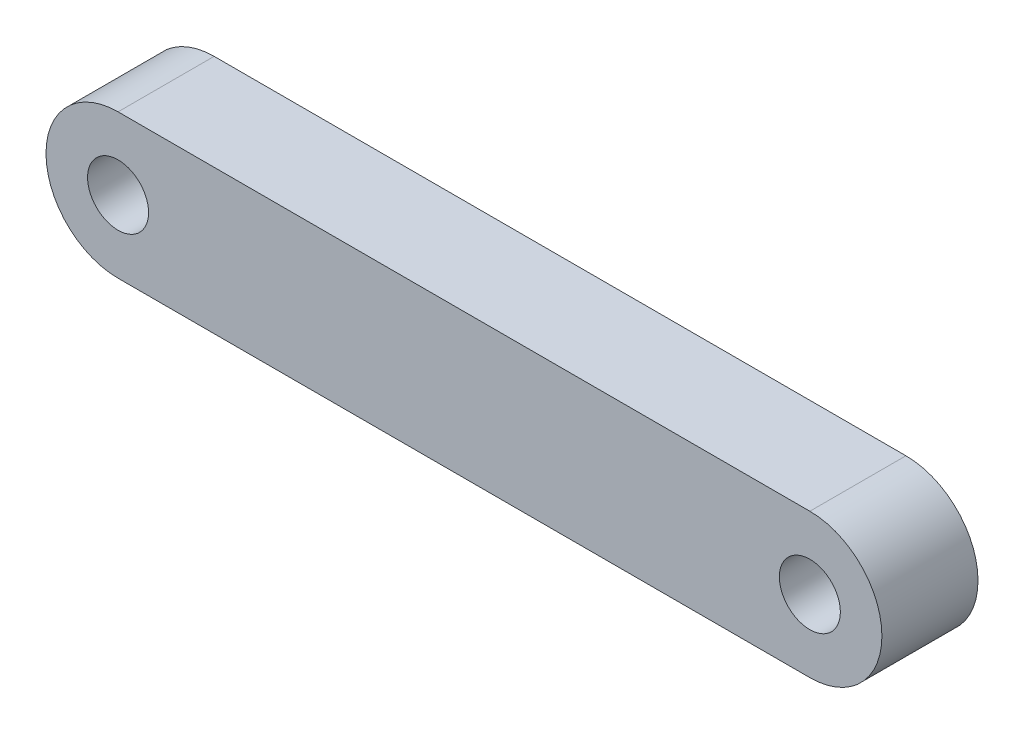
SolidWorks part; units mm, degrees
ref_plane "Front Plane" through (0, 0, 0) normal (0, 0, 1) x (1, 0, 0)
ref_plane "Top Plane" through (0, 0, 0) normal (0, 1, 0) x (1, 0, 0)
ref_plane "Right Plane" through (0, 0, 0) normal (1, 0, 0) x (0, 0, -1)
sketch "Sketch1" plane through (0, 0, 0) normal (0, 0, 1) x (1, 0, 0)
  line L0 (-18, 0) -> (18, 0) construction
  line L1 (-18, 3.75) -> (18, 3.75)
  line L2 (-18, -3.75) -> (18, -3.75)
  arc A0 (-18, 3.75) -> (-18, -3.75) centre (-18, 0) ccw
  arc A1 (18, -3.75) -> (18, 3.75) centre (18, 0) ccw
  point P3 (0, 0)
  dimension "D1" = 36
  dimension "D2" = 7.5
extrude "Boss-Extrude1" add sketch "Sketch1" along normal mid plane 5
sketch "Sketch2" plane through (0, 0, 2.5) normal (0, 0, 1) x (1, 0, 0)
  circle A0 centre (-18, 0) radius 1.5875
  circle A1 centre (18, 0) radius 1.5875
  arc A2 (18, -3.75) -> (18, 3.75) centre (18, 0) ccw construction
  arc A3 (-18, 3.75) -> (-18, -3.75) centre (-18, 0) ccw construction
  dimension "D1" = 3.175
extrude "Cut-Extrude1" cut sketch "Sketch2" against normal through all
